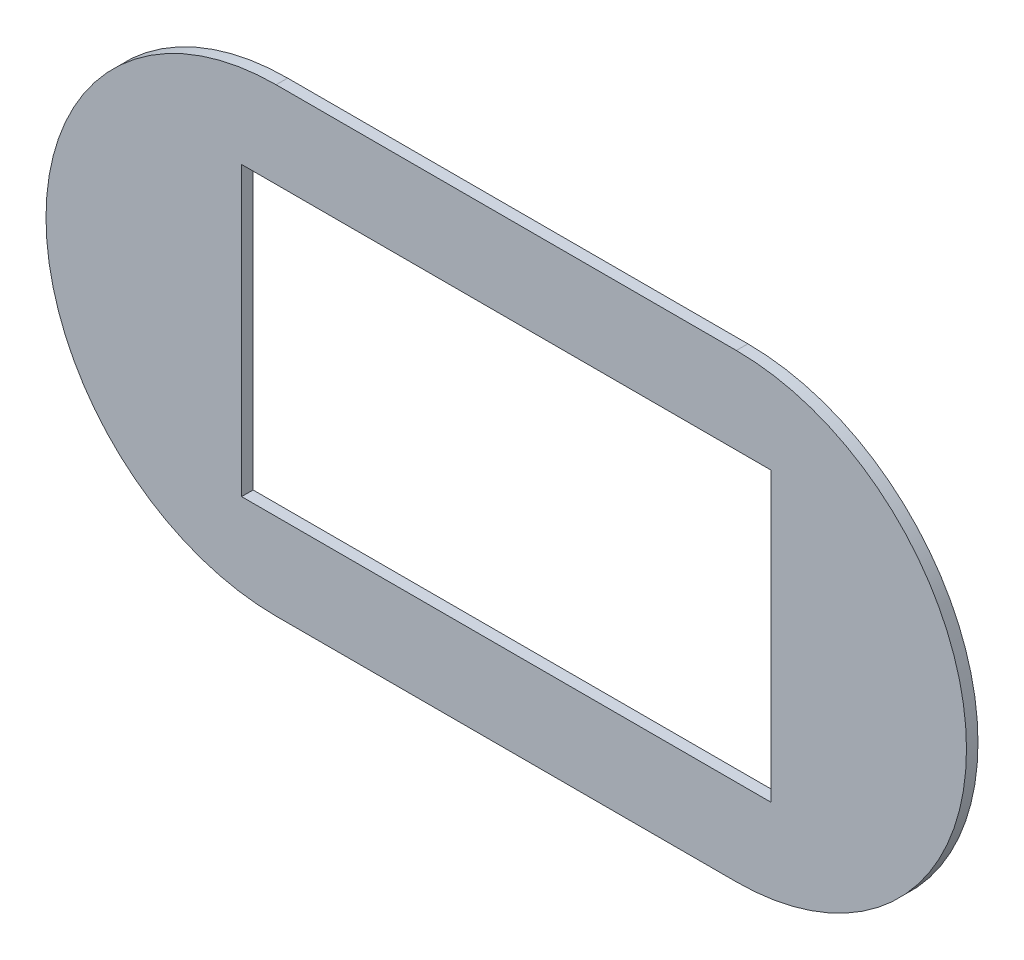
SolidWorks part; units mm, degrees
ref_plane "Спереди" through (0, 0, 0) normal (0, 0, 1) x (1, 0, 0)
ref_plane "Сверху" through (0, 0, 0) normal (0, 1, 0) x (1, 0, 0)
ref_plane "Справа" through (0, 0, 0) normal (1, 0, 0) x (0, 0, -1)
other "Configuration Table"
sketch "Эскиз1" plane through (0, 0, 0) normal (0, 0, 1) x (1, 0, 0)
  line L0 (-40, 0) -> (40, 0) construction
  line L2 (-40, 40) -> (40, 40)
  line L3 (-40, -40) -> (40, -40)
  arc A0 (-40, 40) -> (-40, -40) centre (-40, 0) ccw
  arc A1 (40, -40) -> (40, 40) centre (40, 0) ccw
  point P5 (0, 0)
  dimension "D1" = 80
  dimension "D2" = 160
extrude "Бобышка-Вытянуть1" add sketch "Эскиз1" along normal blind 2
sketch "Эскиз2" plane through (0, 0, 2) normal (0, 0, 1) x (1, 0, 0)
  line L1 (46, -25) -> (-46, -25)
  line L2 (46, -25) -> (46, 25)
  line L3 (46, 25) -> (-46, 25)
  line L4 (-46, -25) -> (-46, 25)
  line L5 (46, -25) -> (-46, 25) construction
  line L6 (46, 25) -> (-46, -25) construction
  point P0 (0, 0)
  dimension "D1" = 50
  dimension "D2" = 92
extrude "Вырез-Вытянуть1" cut sketch "Эскиз2" against normal through all contours L3 L4 L1 L2
